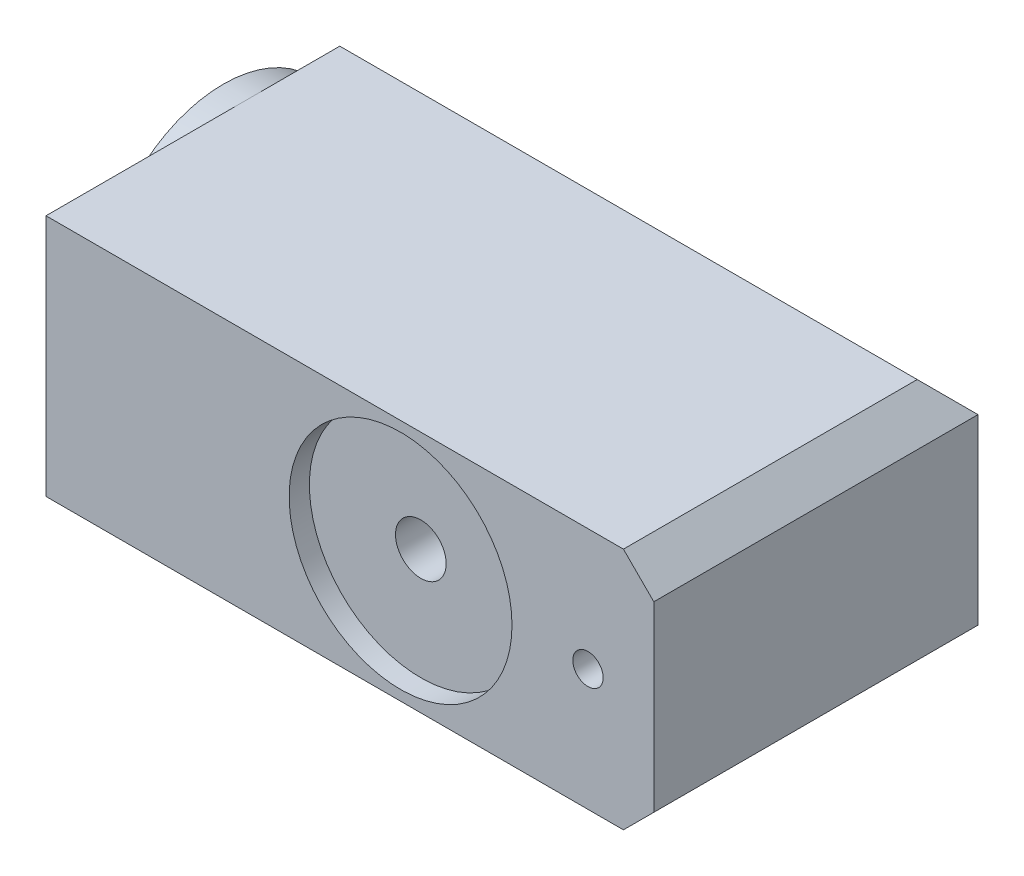
SolidWorks part; units mm, degrees
material "Nickel"
ref_plane "Front Plane" through (0, 0, 0) normal (0, 0, 1) x (1, 0, 0)
ref_plane "Top Plane" through (0, 0, 0) normal (0, 1, 0) x (1, 0, 0)
ref_plane "Right Plane" through (0, 0, 0) normal (1, 0, 0) x (0, 0, -1)
sketch "Sketch1" plane through (0, 0, 0) normal (0, 0, 1) x (1, 0, 0)
  line L1 (-30, 12) -> (30, 12)
  line L2 (-30, 12) -> (-30, -12)
  line L3 (-30, -12) -> (30, -12)
  line L4 (30, 12) -> (30, -12)
  line L5 (-30, 12) -> (30, -12) construction
  line L6 (-30, -12) -> (30, 12) construction
  point P0 (0, 0)
  dimension "D1" = 60
  dimension "D2" = 24
extrude "Boss-Extrude1" add sketch "Sketch1" along normal mid plane 32
chamfer "Chamfer1" distance 3 angle 45 2 edges at (30, -12, 0) (30, 12, 0)
sketch "Sketch2" plane through (0, 0, 16) normal (0, 0, 1) x (1, 0, 0)
  line L0 (30, -9) -> (30, 9) construction
  circle A0 centre (5, 0) radius 11
  point P4 (0, 0)
  dimension "D1" = 22
  dimension "D2" = 25
extrude "Cut-Extrude1" cut sketch "Sketch2" against normal blind 2
sketch "Sketch3" plane through (-30, 0, 0) normal (-1, 0, 0) x (0, 0, 1)
  line L0 (-16, 12) -> (-16, -12) construction
  circle A0 centre (-4, 0) radius 12
  circle A1 centre (-4, 0) radius 9.5
  dimension "D1" = 24
  dimension "D2" = 19
extrude "Boss-Extrude2" add sketch "Sketch3" along normal mid plane 5
sketch "Sketch4" plane through (-30, 0, 0) normal (-1, 0, 0) x (0, 0, 1)
  circle A0 centre (-4, 0) radius 9.5
extrude "Cut-Extrude2" cut sketch "Sketch4" against normal offset from surface (53 mm away) 7 up to face at (30, 0, 0)
chamfer "Chamfer2" distance 3 angle 45 2 edges at (-1.5, -12, -16) (-1.5, 12, -16)
sketch "Sketch5" plane through (0, 0, 16) normal (0, 0, 1) x (1, 0, 0)
  line L0 (30, -9) -> (30, 9) construction
  circle A0 centre (23.5, 0) radius 1.5
  dimension "D1" = 3
  dimension "D2" = 6.5
extrude "Cut-Extrude3" cut sketch "Sketch5" against normal blind 12
hole_wizard "M6 Tapped Hole1" positions "Sketch6" profile "Sketch7" tap size "M6" standard "ISO"
sketch "Sketch6" plane through (0, 0, 14) normal (0, 0, 1) x (1, 0, 0)
  point P0 (5, 0)
sketch "Sketch7" plane through (5, 0, 14) normal (1, 0, 0) x (0, -1, 0)
  line L0 (0, 0) -> (0, 13.5022)
  line L1 (0, 13.5022) -> (2.5, 12)
  line L2 (2.5, 12) -> (2.5, 0)
  line L5 (2.5, 0) -> (0, 0)
  line L10 (0, 13.5022) -> (-2.5, 12) construction
  line L11 (0, -6.35) -> (0, 107.95) construction
  dimension "Tap Drill Dia." = 5
  dimension "Tap Drill Depth" = 12
  dimension "Drill Angle" = 118
cosmetic thread "Hole Thread1" parameters "D1"=12, "D2"=6
